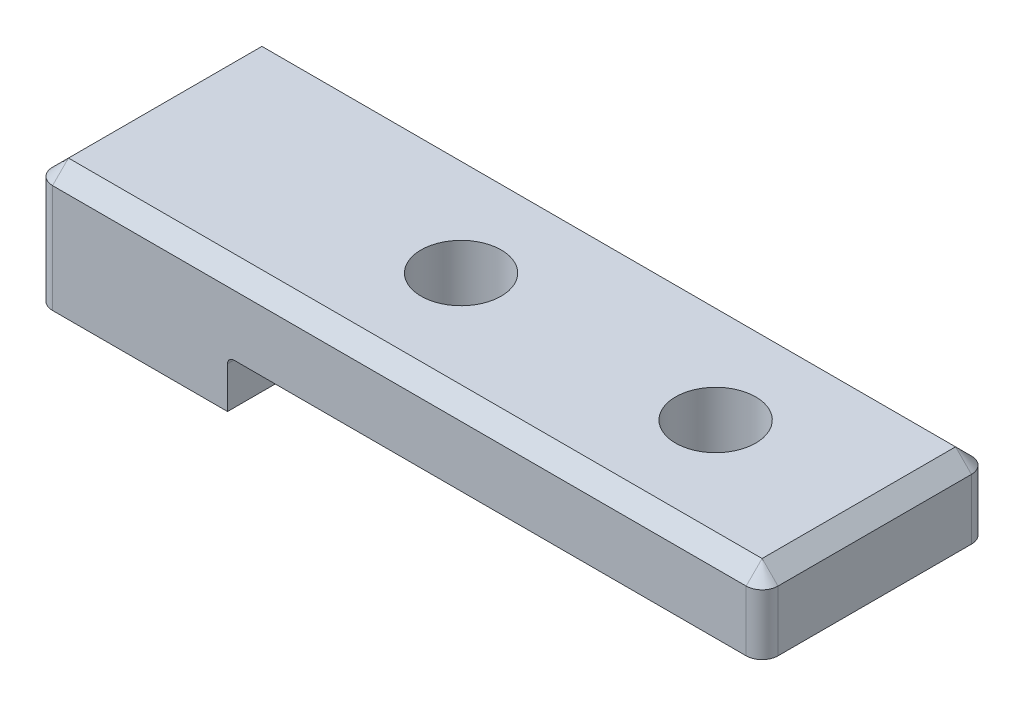
SolidWorks part; units mm, degrees
material "PLA2"
ref_plane "Front Plane" through (0, 0, 0) normal (0, 0, 1) x (1, 0, 0)
ref_plane "Top Plane" through (0, 0, 0) normal (0, 1, 0) x (1, 0, 0)
ref_plane "Right Plane" through (0, 0, 0) normal (1, 0, 0) x (0, 0, -1)
sketch "Sketch1" plane through (0, 0, 0) normal (0, 1, 0) x (1, 0, 0)
  line L0 (0, 0) -> (14.478, 0) construction
  line L1 (-14.478, 4.4958) -> (14.478, 4.4958)
  line L2 (-14.478, 4.4958) -> (-14.478, -4.4958)
  line L3 (-14.478, -4.4958) -> (14.478, -4.4958)
  line L4 (14.478, 4.4958) -> (14.478, -4.4958)
  line L5 (-14.478, 4.4958) -> (14.478, -4.4958) construction
  line L6 (-14.478, -4.4958) -> (14.478, 4.4958) construction
  circle A0 centre (8.128, 0) radius 1.6002
  circle A1 centre (-2.032, 0) radius 1.6002
  point P0 (0, 0)
  dimension "D3" = 3.2004
  dimension "D4" = 3.2004
  dimension "D1" = 28.956
  dimension "D2" = 8.9916
  dimension "D5" = 10.16
  dimension "D6" = 6.35
extrude "Boss-Extrude1" add sketch "Sketch1" along normal blind 3.048
sketch "Sketch2" plane through (0, 0, 4.4958) normal (0, 0, 1) x (1, 0, 0)
  line L0 (-14.478, 0) -> (-14.478, -1.905)
  line L1 (-14.478, -1.905) -> (-6.858, -1.905)
  line L2 (-6.858, -1.905) -> (-6.858, 0)
  line L3 (-14.478, 0) -> (14.478, 0) construction
  line L4 (-14.478, 0) -> (-6.858, 0)
  dimension "D1" = 1.905
  dimension "D2" = 7.62
extrude "Boss-Extrude2" add sketch "Sketch2" against normal blind 6.35
fillet "Fillet1" radius 0.254 2 edges at (-10.668, 0, -1.8542) (-6.858, 0, 1.3208)
fillet "Fillet2" radius 0.635 4 edges at (14.478, 1.524, -4.4958) (14.478, 1.524, 4.4958) (-14.478, 0.5715, 4.4958) (-14.478, 1.524, -4.4958)
chamfer "Chamfer1" distance 0.635 angle 45 8 edges at (14.478, 3.048, 0) (14.292, 3.048, -4.3098) (14.292, 3.048, 4.3098) (0, 3.048, -4.4958) (0, 3.048, 4.4958) (-14.292, 3.048, -4.3098) (-14.292, 3.048, 4.3098) (-14.478, 3.048, 0)
